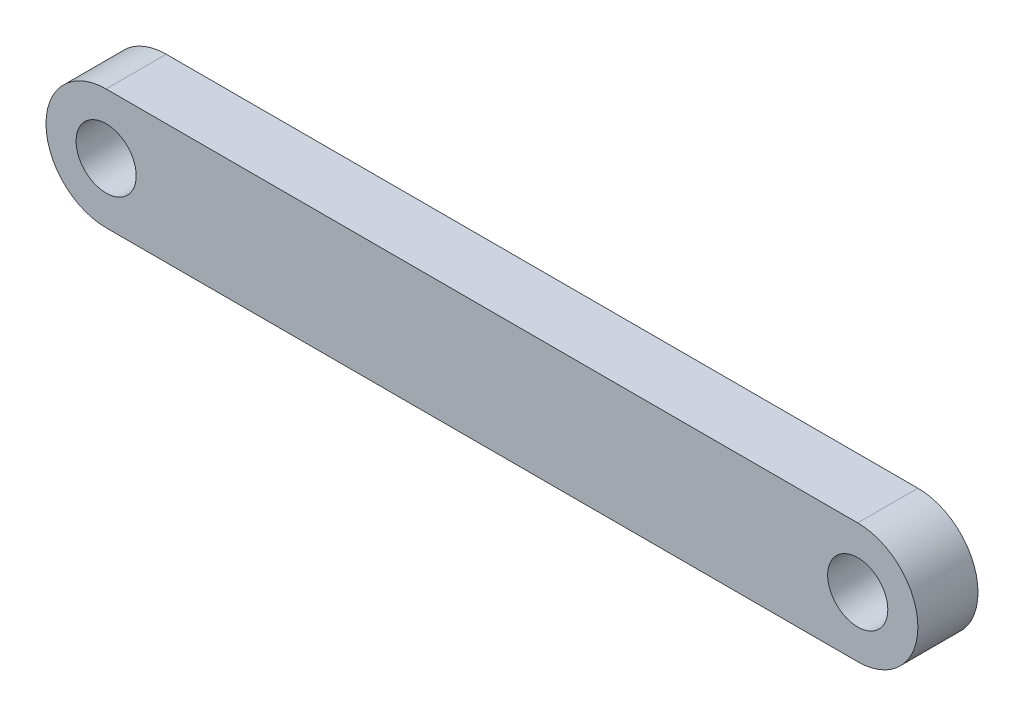
SolidWorks part; units mm, degrees
ref_plane "Front Plane" through (0, 0, 0) normal (0, 0, 1) x (1, 0, 0)
ref_plane "Top Plane" through (0, 0, 0) normal (0, 1, 0) x (1, 0, 0)
ref_plane "Right Plane" through (0, 0, 0) normal (1, 0, 0) x (0, 0, -1)
sketch "Sketch1" plane through (0, 0, 0) normal (0, 0, 1) x (1, 0, 0)
  line L0 (-62.5, 0) -> (62.5, 0) construction
  line L1 (-62.5, 10) -> (62.5, 10)
  line L2 (-62.5, -10) -> (62.5, -10)
  arc A0 (-62.5, 10) -> (-62.5, -10) centre (-62.5, 0) ccw
  arc A1 (62.5, -10) -> (62.5, 10) centre (62.5, 0) ccw
  circle A2 centre (-62.5, 0) radius 5
  circle A3 centre (62.5, 0) radius 5
  point P3 (0, 0)
  dimension "D4" = 10
  dimension "D5" = 10
  dimension "D1" = 125
  dimension "D2" = 20
  dimension "D3" = 62.5
extrude "Boss-Extrude3" add sketch "Sketch1" along normal mid plane 10
